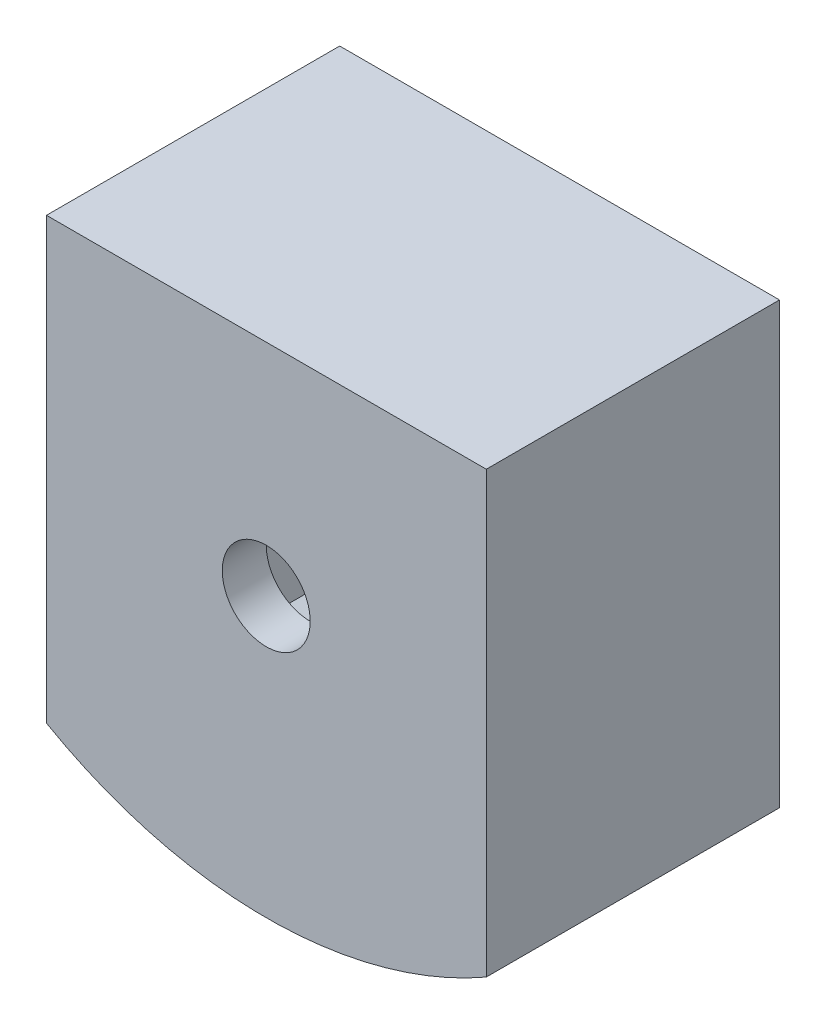
SolidWorks part; units mm, degrees
ref_plane "Front Plane" through (0, 0, 0) normal (0, 0, 1) x (1, 0, 0)
ref_plane "Top Plane" through (0, 0, 0) normal (0, 1, 0) x (1, 0, 0)
ref_plane "Right Plane" through (0, 0, 0) normal (1, 0, 0) x (0, 0, -1)
sketch "Sketch1" plane through (0, 0, 0) normal (0, 0, 1) x (1, 0, 0)
  line L2 (15, -15) -> (15, 15)
  line L3 (15, 15) -> (-15, 15)
  line L4 (-15, -15) -> (-15, 15)
  line L5 (15, -15) -> (-15, 15) construction
  line L6 (15, 15) -> (-15, -15) construction
  arc A3 (-15, -15) -> (15, -15) centre (0, 11.0898) ccw
  point P0 (0, 0)
extrude "Boss-Extrude1" add sketch "Sketch1" along normal blind 20
shell "Shell13" thickness 3
sketch "Sketch3" plane through (0, 0, 17) normal (0, 0, -1) x (-1, 0, 0)
  circle A0 centre (0.0103, 0.0076) radius 3
extrude "Cut-Extrude2" cut sketch "Sketch3" against normal blind 3
sketch "Sketch4" plane through (0, 0, 0) normal (0, 0, -1) x (-1, 0, 0)
  line L0 (12, 12) -> (12, -13.2024) construction
  line L1 (-5, 14) -> (5, 14)
  line L2 (-5, 14) -> (-5, 13)
  line L3 (-5, 13) -> (5, 13)
  line L4 (5, 14) -> (5, 13)
  line L5 (-14, 5) -> (-13, 5)
  line L6 (-14, 5) -> (-14, -5)
  line L7 (-14, -5) -> (-13, -5)
  line L8 (-13, 5) -> (-13, -5)
  line L9 (-3.5, -17) -> (3.5, -17)
  line L10 (-3.5, -17) -> (-3.5, -18)
  line L11 (-3.5, -18) -> (3.5, -18)
  line L12 (3.5, -17) -> (3.5, -18)
  line L13 (13, 5) -> (14, 5)
  line L14 (13, 5) -> (13, -5)
  line L15 (13, -5) -> (14, -5)
  line L16 (14, 5) -> (14, -5)
  line L17 (-12, -13.2024) -> (-12, 12) construction
  line L18 (-12, 12) -> (12, 12) construction
  point P16 (0, -17)
  point P18 (-13, 0)
  point P19 (13, 0)
  point P20 (0, 13)
  dimension "D1" = 1
  dimension "D2" = 1
  dimension "D3" = 1
  dimension "D4" = 17
extrude "Cut-Extrude3" cut sketch "Sketch4" against normal blind 5
